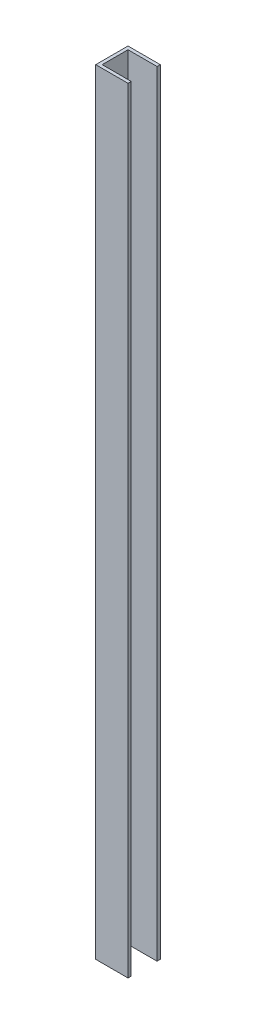
SolidWorks part; units mm, degrees
ref_plane "前视基准面" through (0, 0, 0) normal (0, 0, 1) x (1, 0, 0)
ref_plane "上视基准面" through (0, 0, 0) normal (0, 1, 0) x (1, 0, 0)
ref_plane "右视基准面" through (0, 0, 0) normal (1, 0, 0) x (0, 0, -1)
sketch "草图1" plane through (0, 0, 0) normal (0, 1, 0) x (1, 0, 0)
  line L0 (-7.8316, 0) -> (6.4823, 0) construction
  line L1 (0, 8.9462) -> (0, -8.6528) construction
  line L2 (4, 4) -> (5, 4)
  line L3 (-4, 4) -> (4, 4)
  line L4 (-4, 4) -> (-4, -4)
  line L5 (-4, -4) -> (4, -4)
  line L6 (5, -4) -> (5, -5)
  line L9 (-5, 5) -> (5, 5)
  line L10 (-5, 5) -> (-5, -5)
  line L11 (-5, -5) -> (5, -5)
  line L12 (5, 5) -> (5, 4)
  line L15 (4, -4) -> (5, -4)
  point P5 (0, 0)
  point P10 (0, 0)
  dimension "D1" = 10
  dimension "D2" = 8
extrude "凸台-拉伸1" add sketch "草图1" along normal blind 240
